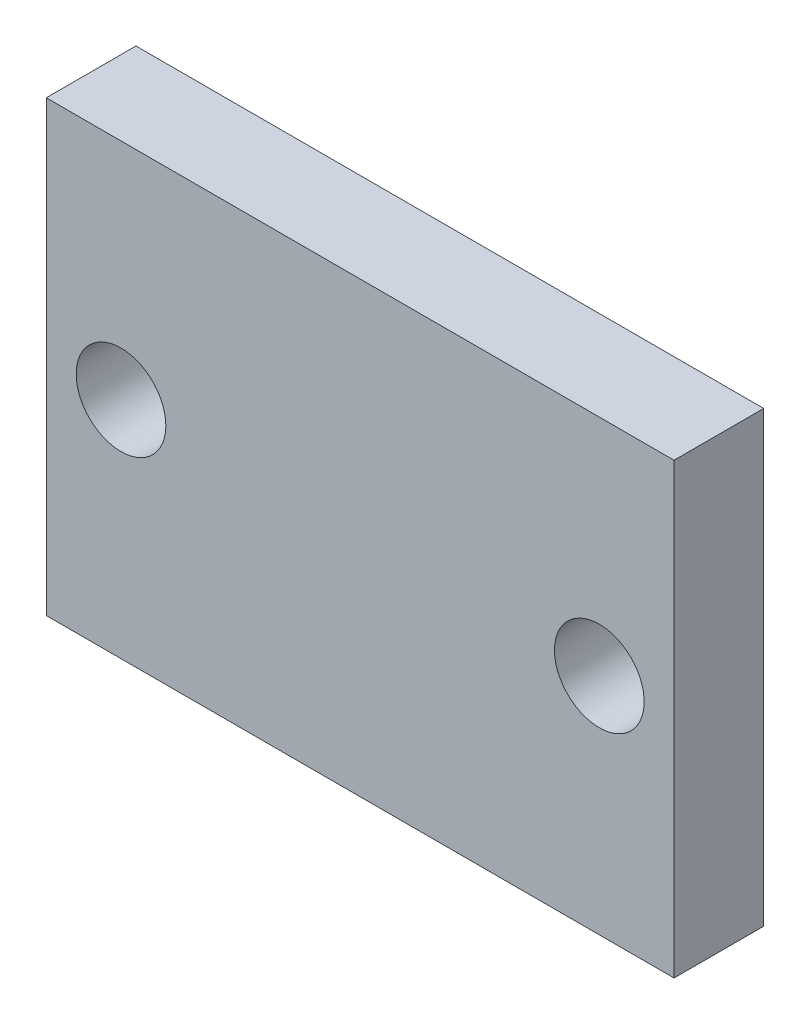
SolidWorks part; units mm, degrees
material "环氧树脂,未充填"
ref_plane "前视基准面" through (0, 0, 0) normal (0, 0, 1) x (1, 0, 0)
ref_plane "上视基准面" through (0, 0, 0) normal (0, 1, 0) x (1, 0, 0)
ref_plane "右视基准面" through (0, 0, 0) normal (1, 0, 0) x (0, 0, -1)
sketch "草图1" plane through (0, 0, 0) normal (0, 0, 1) x (1, 0, 0)
  line L0 (0, 7.5) -> (0, -7.5) construction
  line L1 (-10.5, 7.5) -> (10.5, 7.5)
  line L2 (-10.5, 7.5) -> (-10.5, -7.5)
  line L3 (-10.5, -7.5) -> (10.5, -7.5)
  line L4 (10.5, 7.5) -> (10.5, -7.5)
  line L5 (-10.5, 7.5) -> (10.5, -7.5) construction
  line L6 (-10.5, -7.5) -> (10.5, 7.5) construction
  circle A0 centre (-8, 0) radius 1.5
  circle A1 centre (8, 0) radius 1.5
  point P0 (0, 0)
  dimension "D3" = 8
  dimension "D4" = 3
  dimension "D1" = 21
  dimension "D2" = 15
extrude "凸台-拉伸1" add sketch "草图1" along normal blind 3
